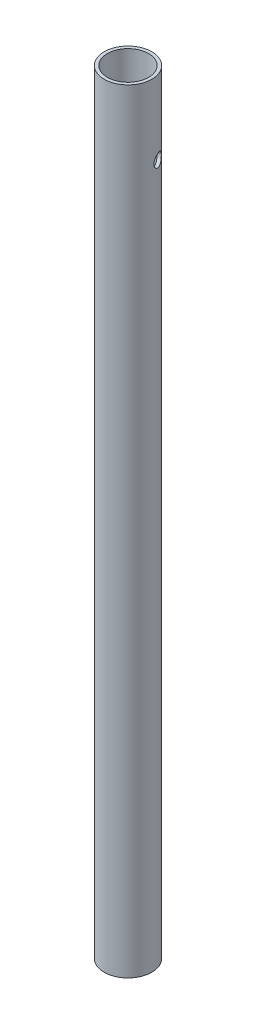
SolidWorks part; units mm, degrees
ref_plane "Спереди" through (0, 0, 0) normal (0, 0, 1) x (1, 0, 0)
ref_plane "Сверху" through (0, 0, 0) normal (0, 1, 0) x (1, 0, 0)
ref_plane "Справа" through (0, 0, 0) normal (1, 0, 0) x (0, 0, -1)
sketch "Эскиз1" plane through (0, 0, 0) normal (0, 1, 0) x (1, 0, 0)
  circle A0 centre (0, 0) radius 13
  circle A1 centre (0, 0) radius 15
  dimension "D1" = 26
  dimension "D2" = 30
extrude "Вытянуть1" add sketch "Эскиз1" along normal blind 487
sketch "Эскиз5" plane through (-19.1776, 0, 7.2437) normal (-0.9355, 0, 0.3534) x (0.3534, 0, 0.9355)
  line L0 (15, 487) -> (-15, 487) construction
  circle A0 centre (0, 440) radius 4
  dimension "D1" = 47
extrude "Вырез-Вытянуть1" cut sketch "Эскиз5" against normal mid plane 95
